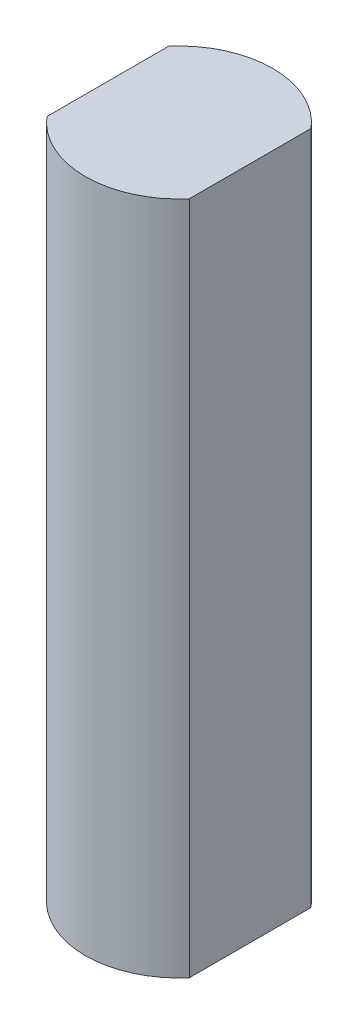
SolidWorks part; units mm, degrees
ref_plane "Front Plane" through (0, 0, 0) normal (0, 0, 1) x (1, 0, 0)
ref_plane "Top Plane" through (0, 0, 0) normal (0, 1, 0) x (1, 0, 0)
ref_plane "Right Plane" through (0, 0, 0) normal (1, 0, 0) x (0, 0, -1)
sketch "Sketch1" plane through (0, 0, 0) normal (0, 1, 0) x (1, 0, 0)
  line L0 (0, 0) -> (2.5, 0) construction
  line L1 (2.5, 0) -> (0, 2.5) construction
  line L2 (0, 2.5) -> (0, 0) construction
  line L3 (1.9, -1.6248) -> (1.9, 1.6248)
  line L4 (-1.9, -1.6248) -> (-1.9, 1.6248)
  arc A0 (-1.9, -1.6248) -> (1.9, -1.6248) centre (0, 0) ccw
  arc A1 (1.9, 1.6248) -> (-1.9, 1.6248) centre (0, 0) ccw
  point P8 (1.9, 0)
  dimension "D1" = 5
  dimension "D2" = 1.9
extrude "Boss-Extrude1" add sketch "Sketch1" along normal blind 18 contours L4 A1 L3 A0
